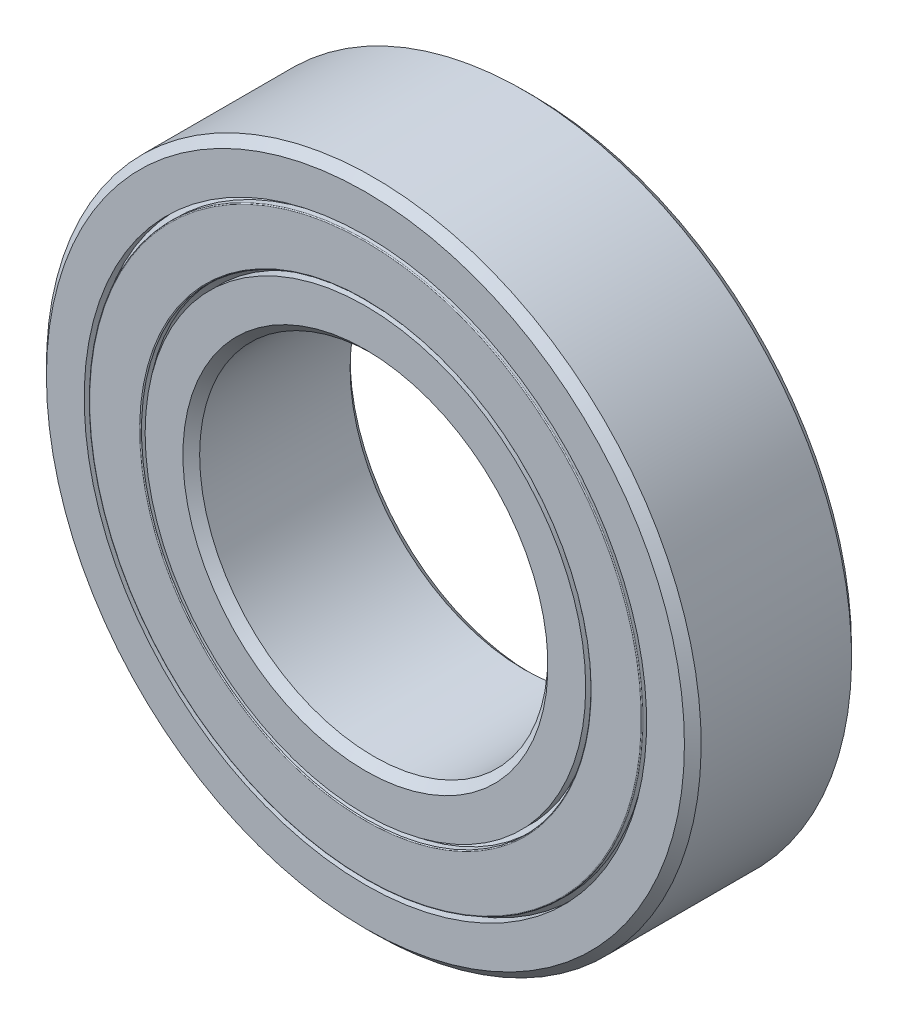
SolidWorks part; units mm, degrees
ref_plane "Front Plane" through (0, 0, 0) normal (0, 0, 1) x (1, 0, 0)
ref_plane "Top Plane" through (0, 0, 0) normal (0, 1, 0) x (1, 0, 0)
ref_plane "Right Plane" through (0, 0, 0) normal (1, 0, 0) x (0, 0, -1)
sketch "Sketch1" plane through (0, 0, 0) normal (0, 0, 1) x (1, 0, 0)
  line L0 (-23.5, 0) -> (23.5, 0) construction
  line L1 (-12.5, 0) -> (12.5, 0) construction
  circle A0 centre (0, 0) radius 12.5 construction
  circle A1 centre (0, 0) radius 23.5 construction
  point P3 (0, 0)
  point P6 (0, 0)
  point P7 (0, -12.5)
  point P11 (0, -23.5)
  point P12 (0, 12.5)
  point P13 (0, 23.5)
  dimension "OD" = 47
  dimension "ID" = 25
sketch "Sketch2" plane through (0, 0, 0) normal (1, 0, 0) x (0, 0, -1)
  line L0 (-6, 23.5) -> (6, 23.5) construction
  line L1 (0, 23.5) -> (0, -23.5) construction
  line L2 (5.4, 23.5) -> (-5.4, 23.5)
  line L3 (-5.4, 23.5) -> (-6, 22.9)
  line L4 (-6, 22.9) -> (-6, 20.1875)
  line L5 (-6, 20.1875) -> (-2.6667, 20.1875)
  line L6 (6, 20.1875) -> (2.6667, 20.1875)
  line L7 (6, 22.9) -> (6, 20.1875)
  line L8 (5.4, 23.5) -> (6, 22.9)
  line L9 (0, 23.5) -> (0, 18) construction
  line L10 (0, 18) -> (0, 12.5) construction
  line L11 (0, 23.5) -> (0, -23.5) construction
  line L12 (-6, 0) -> (6, 0) construction
  line L13 (6, 12.5) -> (-6, 12.5) construction
  line L14 (0, 21.4491) -> (0, 14.5509) construction
  line L15 (-6, -12.5) -> (6, -12.5) construction
  line L16 (-6, 12.5) -> (-6, -12.5) construction
  line L17 (6, 23.5) -> (6, -23.5) construction
  line L18 (-6, 20.1875) -> (-6, 19.9688) construction
  line L19 (-6, 19.9688) -> (-6, 19.75) construction
  line L20 (-6, 19.75) -> (-6, 19.5312) construction
  line L21 (-6, 19.5312) -> (-6, 19.3125) construction
  line L22 (-6, 19.3125) -> (-6, 19.0938) construction
  line L24 (-4.3333, 20.1875) -> (-4.3333, 18) construction
  arc A0 (-2.6667, 20.1875) -> (2.6667, 20.1875) centre (0, 18) cw
  circle A1 centre (0, 18) radius 3.4491 construction
  point P14 (0, 12.5)
  point P17 (0, 0)
  point P21 (0, 23.5)
  point P29 (0, 12.5)
  point P30 (0, -12.5)
  point P46 (-4.3333, 19.0938)
  dimension "Width" = 12
  dimension "D1" = 45
  dimension "D2" = 0.6
  dimension "D3" = 5.3333
  dimension "D4" = 2.1875
  dimension "For Shaft Diameter" = 25
  dimension "For Housing ID" = 47
sketch "Sketch3" plane through (0, 0, 0) normal (1, 0, 0) x (0, 0, -1)
  line L0 (5.4, 23.5) -> (6, 22.9) construction
  line L1 (6, 22.9) -> (6, 20.1875) construction
  line L2 (6, 20.1875) -> (2.6667, 20.1875) construction
  line L3 (-6, 20.1875) -> (-2.6667, 20.1875) construction
  line L4 (-6, 22.9) -> (-6, 20.1875) construction
  line L5 (-5.4, 23.5) -> (-6, 22.9) construction
  line L6 (5.4, 23.5) -> (-5.4, 23.5) construction
  line L7 (5.4, 23.5) -> (6, 22.9)
  line L8 (6, 22.9) -> (6, 20.1875)
  line L9 (6, 20.1875) -> (2.6667, 20.1875)
  line L10 (-6, 20.1875) -> (-2.6667, 20.1875)
  line L11 (-6, 22.9) -> (-6, 20.1875)
  line L12 (-5.4, 23.5) -> (-6, 22.9)
  line L13 (5.4, 23.5) -> (-5.4, 23.5)
  arc A0 (2.6667, 20.1875) -> (-2.6667, 20.1875) centre (0, 18) ccw construction
  arc A1 (2.6667, 20.1875) -> (-2.6667, 20.1875) centre (0, 18) ccw
revolve "Revolve1" add sketch "Sketch3" angle 360 about L12
sketch "Sketch4" plane through (0, 0, 0) normal (1, 0, 0) x (0, 0, -1)
  line L0 (0, 23.5) -> (0, -23.5) construction
  line L1 (0, 23.5) -> (0, -23.5) construction
  line L2 (-5.4, 12.5) -> (-6, 13.1)
  line L3 (-6, 13.1) -> (-6, 15.8125)
  line L5 (-6, 15.8125) -> (-2.6667, 15.8125)
  line L6 (-5.4, 12.5) -> (5.4, 12.5)
  line L8 (5.4, 12.5) -> (6, 13.1)
  line L10 (6, 13.1) -> (6, 15.8125)
  line L11 (6, 15.8125) -> (2.6667, 15.8125)
  line L12 (-6, 22.9) -> (-6, 20.1875) construction
  line L13 (5.4, 23.5) -> (6, 22.9) construction
  line L15 (6, -22.9) -> (6, 22.9) construction
  line L16 (5.4, 23.5) -> (5.4, -23.5) construction
  arc A1 (2.6667, 15.8125) -> (-2.6667, 15.8125) centre (0, 18) cw
  circle A2 centre (0, 18) radius 3.4491 construction
  point P1 (0, 12.5)
revolve "Revolve2" add sketch "Sketch4" angle 360 about L12
sketch "Sketch5" plane through (0, 0, 0) normal (1, 0, 0) x (0, 0, -1)
  line L0 (-3.4491, 18) -> (3.4491, 18)
  arc A2 (-3.4491, 18) -> (3.4491, 18) centre (0, 18) cw
  arc A3 (2.6667, 20.1875) -> (-2.6667, 20.1875) centre (0, 18) ccw construction
revolve "Revolve3" add sketch "Sketch5" angle 360 about L0
sketch "Sketch6" plane through (0, 0, 0) normal (1, 0, 0) x (0, 0, -1)
  line L0 (-6, 20.1875) -> (-6, 19.0937) construction
  line L1 (-6, 22.9) -> (-6, -22.9) construction
  line L2 (-6, 19.0937) -> (-6, 18) construction
  line L3 (-6, 18) -> (-6, 16.9062) construction
  line L4 (-6, 16.9062) -> (-6, 15.8125) construction
  line L5 (-6, 19.0937) -> (-5.5452, 19.0937) construction
  line L7 (-3.2711, 19.0938) -> (-3.2711, 16.9063) construction
  line L8 (-5.5452, 19.0937) -> (-5.0904, 19.0937) construction
  line L10 (0, 23.5) -> (0, -23.5) construction
  line L11 (0, 23.5) -> (0, -23.5) construction
  line L12 (-5.0904, 19.0937) -> (-4.6355, 19.0937) construction
  line L13 (-4.6355, 19.0937) -> (-4.1807, 19.0937) construction
  line L14 (-4.1807, 19.0937) -> (-3.7259, 19.0937) construction
  line L15 (-3.7259, 19.0937) -> (-3.2711, 19.0938) construction
  line L16 (-3.2711, 19.0938) -> (-3.7259, 19.0937)
  line L17 (-3.7259, 16.9063) -> (-4.1807, 16.9063) construction
  line L18 (-3.7259, 16.9063) -> (-3.2711, 16.9063)
  line L19 (-4.1807, 16.9063) -> (-4.1807, 19.0937) construction
  line L20 (-3.9533, 19.0937) -> (-3.9533, 16.9063) construction
  circle A0 centre (0, 18) radius 3.4491 construction
  circle A1 centre (0, 18) radius 3.4491 construction
  arc A2 (-3.7259, 19.0937) -> (-3.7259, 16.9063) centre (-1.2094, 18) ccw
  arc A3 (-3.2711, 19.0938) -> (-3.2711, 16.9063) centre (0, 18) ccw
  point P28 (-3.9533, 18)
revolve "Revolve4" add sketch "Sketch6" angle 360 about L11
pattern_circular "CirPattern1" count 10 over 360 about axis through (0, 0, 0) along (0, 0, 1) of bodies 134 104
sketch "Sketch7" plane through (0, 0, 0) normal (0, 0, 1) x (1, 0, 0)
  line L0 (0, 15.8125) -> (0, 16.5417) construction
  line L1 (0, 14.5509) -> (0, 21.4491) construction
  line L2 (0, 16.5417) -> (0, 17.2708) construction
  line L3 (0, 17.2708) -> (0, 18) construction
  line L4 (0, 18) -> (0, 18.7292) construction
  line L5 (0, 18.7292) -> (0, 19.4583) construction
  line L6 (0, 19.4583) -> (0, 20.1875) construction
  line L7 (0, 22.9) -> (0, 20.1875) construction
  line L8 (0, 23.5) -> (0, -23.5) construction
  circle A0 centre (0, 0) radius 15.8125 construction
  circle A1 centre (0, 0) radius 18
  circle A2 centre (0, 0) radius 19.0938
  point P19 (0, 19.0938)
extrude "Boss-Extrude1" add sketch "Sketch7" along normal mid plane 2 separate body
sketch "Sketch8" plane through (0, 0, 0) normal (1, 0, 0) x (0, 0, -1)
  line L0 (-6, 19.9688) -> (-6, 19.75) construction
  line L1 (-6, 19.8594) -> (-5.5556, 19.8594)
  line L2 (-6, 19.8594) -> (-6, 16.1406)
  line L3 (-6, 16.1406) -> (-5.5556, 16.1406)
  line L4 (-5.3333, 19.8594) -> (-5.3333, 16.1406)
  line L5 (0, 23.5) -> (0, 18) construction
  line L10 (-5.5556, 19.8594) -> (-5.3333, 20.1875)
  line L11 (-6, 20.1875) -> (-2.6667, 20.1875) construction
  line L12 (-5.3333, 20.1875) -> (-5.3333, 19.8594)
  line L13 (-5.5556, 16.1406) -> (-5.3333, 15.8125)
  line L14 (-5.3333, 15.8125) -> (-5.3333, 16.1406)
  line L15 (-6, 20.1875) -> (-5.7778, 20.1875) construction
  line L16 (6, 19.8594) -> (6, 16.1406)
  line L17 (6, 16.1406) -> (5.5556, 16.1406)
  line L18 (5.5556, 16.1406) -> (5.3333, 15.8125)
  line L19 (5.3333, 15.8125) -> (5.3333, 16.1406)
  line L20 (5.3333, 19.8594) -> (5.3333, 16.1406)
  line L21 (5.3333, 20.1875) -> (5.3333, 19.8594)
  line L22 (5.5556, 19.8594) -> (5.3333, 20.1875)
  line L23 (6, 19.8594) -> (5.5556, 19.8594)
  line L24 (-5.7778, 20.1875) -> (-5.5556, 20.1875) construction
  line L25 (-5.5556, 20.1875) -> (-5.3333, 20.1875) construction
  line L27 (-6, 15.8125) -> (-2.6667, 15.8125) construction
  point P23 (-6, 19.8594)
  dimension "D1" = 0.6667
revolve "Revolve5" add sketch "Sketch8" angle 360 about L12
fillet "Fillet1" radius 0.0667 2 edges at (0, -19.8594, 6) (0, -16.1406, 6)
fillet "Fillet2" radius 0.0667 2 edges at (0, -16.1406, -6) (0, -19.8594, -6)
equation "\"D2@Sketch2\" = \"Width@Sketch2\" * .05"
equation "\"D3@Sketch2\" = \"Width@Sketch2\" / 2.25"
equation "\"D4@Sketch2\"=( \"OD@Sketch1\" - \"Width@Sketch2\" )  *.5*.125"
equation "\"D1@Boss-Extrude1\" = \"Width@Sketch2\" / 6"
equation "\"D1@Sketch8\"=(\"Width@Sketch2\"-\"D3@Sketch2\")*.5*.2"
equation "\"D1@Fillet1\"=\"d1@sketch8\"*.1"
equation "\"D1@Fillet2\"=\"d1@fillet1\""
